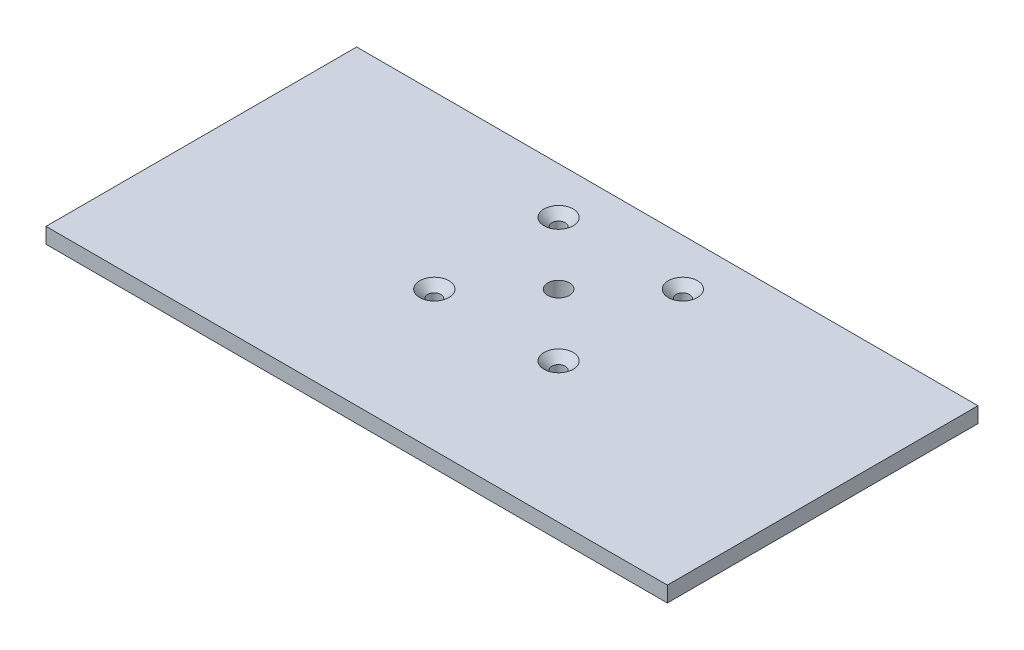
SolidWorks part; units mm, degrees
ref_plane "Front Plane" through (0, 0, 0) normal (0, 0, 1) x (1, 0, 0)
ref_plane "Top Plane" through (0, 0, 0) normal (0, 1, 0) x (1, 0, 0)
ref_plane "Right Plane" through (0, 0, 0) normal (1, 0, 0) x (0, 0, -1)
sketch "Sketch1" plane through (0, 0, 0) normal (0, 1, 0) x (1, 0, 0)
  line L1 (-133.1959, 51.134) -> (66.8041, 51.134)
  line L2 (-133.1959, 51.134) -> (-133.1959, -48.866)
  line L3 (-133.1959, -48.866) -> (66.8041, -48.866)
  line L4 (66.8041, 51.134) -> (66.8041, -48.866)
  dimension "D1" = 100
  dimension "D2" = 200
extrude "Boss-Extrude1" add sketch "Sketch1" along normal blind 5 contours L1 L4 L3 L2
sketch "Sketch2" plane through (0, 5, 0) normal (0, 1, 0) x (1, 0, 0)
  line L0 (-33.1959, 51.134) -> (-33.1959, 36.134)
  line L5 (-133.1959, 51.134) -> (66.8041, 51.134) construction
  line L6 (-33.1959, 36.134) -> (-13.1959, 36.134)
  line L7 (-13.1959, 36.134) -> (-13.1959, -3.866)
  line L8 (-13.1959, -3.866) -> (-53.1959, -3.866)
  line L9 (-53.1959, -3.866) -> (-53.1959, 36.134)
  line L10 (-53.1959, 36.134) -> (-33.1959, 36.134)
  line L11 (-33.1959, 36.134) -> (-33.1959, 16.134)
  circle A0 centre (-33.1959, 16.134) radius 3.5
  dimension "D5" = 20
  dimension "D1" = 20
  dimension "D2" = 40
  dimension "D3" = 40
  dimension "D4" = 15
hole_wizard "CSK for M4 Flat Head Machine Screw1" positions "3DSketch1" profile "Sketch7" countersink size "M4" standard "ANSI Metric"
sketch3d "3DSketch1"
  point P0 (-53.1959, 5, -36.134)
  point P3 (-13.1959, 5, -36.134)
  point P6 (-13.1959, 5, 3.866)
  point P9 (-53.1959, 5, 3.866)
sketch "Sketch7" plane through (-53.1959, 5, -36.134) normal (1, 0, 0) x (0, 0, 1)
  line L0 (0, 0) -> (0, 7.2919)
  line L1 (0, 7.2919) -> (2.15, 6)
  line L2 (2.15, 6) -> (2.15, 2.55)
  line L3 (2.15, 2.55) -> (4.7, 0)
  line L5 (4.7, 0) -> (0, 0)
  line L6 (-2.15, 2.55) -> (-4.7, 0) construction
  line L10 (0, 7.2919) -> (-2.15, 6) construction
  line L11 (0, -6.35) -> (0, 107.95) construction
  dimension "Hole Dia." = 4.3
  dimension "Hole Depth" = 6
  dimension "Near C'Sink Dia." = 9.4
  dimension "Near C'Sink Angle" = 90
  dimension "Drill Angle" = 118
extrude "Cut-Extrude1" cut sketch "Sketch2" against normal blind 5 contours A0
